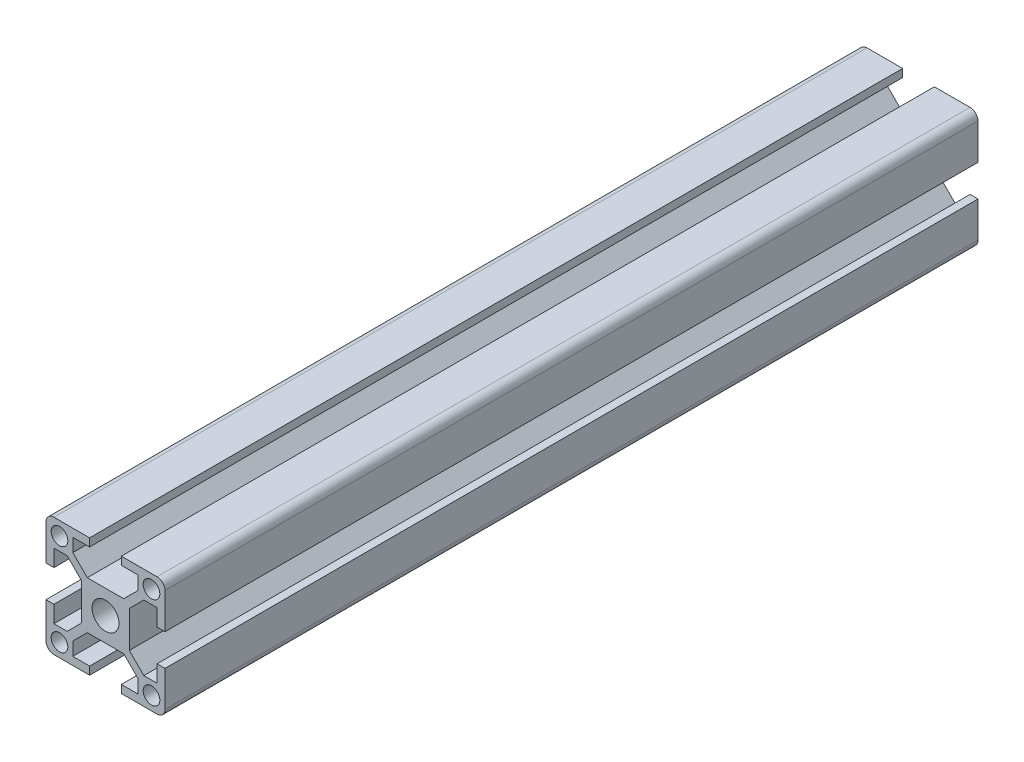
SolidWorks part; units mm, degrees
material "6063-O, Extruded Rod (SS)"
ref_plane "Front Plane" through (0, 0, 0) normal (0, 0, 1) x (1, 0, 0)
ref_plane "Top Plane" through (0, 0, 0) normal (0, 1, 0) x (1, 0, 0)
ref_plane "Right Plane" through (0, 0, 0) normal (1, 0, 0) x (0, 0, -1)
sketch "Sketch1" plane through (0, 0, 0) normal (0, 0, 1) x (1, 0, 0)
  line L0 (-4, 15) -> (-4, -15) construction
  line L1 (15, -15) -> (4, -15)
  line L2 (15, -15) -> (15, -4)
  line L3 (15, 15) -> (4, 15)
  line L4 (-15, -15) -> (-15, -4)
  line L5 (15, -15) -> (-15, 15) construction
  line L6 (15, 15) -> (-15, -15) construction
  line L7 (0, 15) -> (0, -15) construction
  line L8 (4, 15) -> (4, -15) construction
  line L9 (-8.25, 15) -> (-8.25, -15) construction
  line L10 (8.25, 15) -> (8.25, -15) construction
  line L11 (8.25, 13) -> (8.25, 9.6642)
  line L12 (4.5858, -6) -> (-4.5858, -6)
  line L13 (6, -4.5858) -> (6, 4.5858)
  line L14 (4.5858, 6) -> (-4.5858, 6)
  line L15 (-6, -4.5858) -> (-6, 4.5858)
  line L16 (6, -6) -> (-6, 6) construction
  line L17 (6, 6) -> (-6, -6) construction
  line L20 (-13, 8.25) -> (-9.6642, 8.25)
  line L21 (-8.25, 13) -> (-8.25, 9.6642)
  line L22 (-14.95, 14.95) -> (-8.25, 8.25) construction
  line L23 (-14.95, 8.25) -> (-8.25, 14.95) construction
  line L24 (-10.2, 13) -> (-10.0348, 13)
  line L25 (-13, 10.2) -> (-13, 10.0348)
  line L26 (-8.25, -13) -> (-4, -13)
  line L27 (13, 8.25) -> (13, 4)
  line L28 (-13, 13) -> (13, -13) construction
  line L29 (-13, -13) -> (13, 13) construction
  line L30 (13, 8.25) -> (9.6642, 8.25)
  line L31 (13, -8.25) -> (9.6642, -8.25)
  line L32 (8.25, -13) -> (8.25, -9.6642)
  line L33 (-8.25, -13) -> (-8.25, -9.6642)
  line L34 (-13, -8.25) -> (-9.6642, -8.25)
  line L35 (-8.25, 8.25) -> (-6, 6)
  line L36 (-9.6642, 8.25) -> (-6, 4.5858)
  line L37 (-8.25, 9.6642) -> (-4.5858, 6)
  line L38 (-8.9571, 7.5429) -> (-6.7071, 5.2929) construction
  line L39 (-7.5429, 8.9571) -> (-5.2929, 6.7071) construction
  line L40 (-4, 15) -> (-4, 13)
  line L41 (4, 15) -> (4, 13)
  line L42 (8.25, 9.6642) -> (4.5858, 6)
  line L43 (9.6642, 8.25) -> (6, 4.5858)
  line L44 (15, 4) -> (13, 4)
  line L45 (15, -4) -> (13, -4)
  line L46 (9.6642, -8.25) -> (6, -4.5858)
  line L47 (8.25, -9.6642) -> (4.5858, -6)
  line L48 (4, -15) -> (4, -13)
  line L49 (-4, -15) -> (-4, -13)
  line L50 (-8.25, -9.6642) -> (-4.5858, -6)
  line L51 (-9.6642, -8.25) -> (-6, -4.5858)
  line L52 (-15, -4) -> (-13, -4)
  line L53 (-15, 4) -> (-13, 4)
  line L54 (-15, 4) -> (-15, 15)
  line L55 (-13, -4) -> (-13, -8.25)
  line L56 (4, 13) -> (8.25, 13)
  line L57 (-4, 15) -> (-15, 15)
  line L58 (13, -4) -> (13, -8.25)
  line L59 (15, 4) -> (15, 15)
  line L60 (-8.25, 13) -> (-4, 13)
  line L61 (-13, 8.25) -> (-13, 4)
  line L62 (4, -13) -> (8.25, -13)
  line L63 (-4, -15) -> (-15, -15)
  circle A0 centre (0, 0) radius 3.4
  circle A1 centre (-11.6, 11.6) radius 2.1
  circle A2 centre (11.6, 11.6) radius 2.1
  circle A3 centre (11.6, -11.6) radius 2.1
  circle A4 centre (-11.6, -11.6) radius 2.1
  point P0 (0, 0)
  point P19 (-11.6, 15)
  point P52 (0, 0)
  point P87 (0, 0)
  dimension "D3" = 6.8
  dimension "D9" = 4.2
  dimension "D1" = 30
  dimension "D2" = 30
  dimension "D4" = 11
  dimension "D5" = 8.25
  dimension "D6" = 11.6
  dimension "D7" = 3.4
  dimension "D8" = 3.4
  dimension "D10" = 12
  dimension "D11" = 2
  dimension "D13" = 1
  dimension "D14" = 1
  dimension "D12" = 4
  dimension "D15" = 4
extrude "Boss-Extrude1" add sketch "Sketch1" along normal blind 205
fillet "Fillet1" radius 2 4 edges at (-15, -15, 102.5) (15, -15, 102.5) (-15, 15, 102.5) (15, 15, 102.5)
